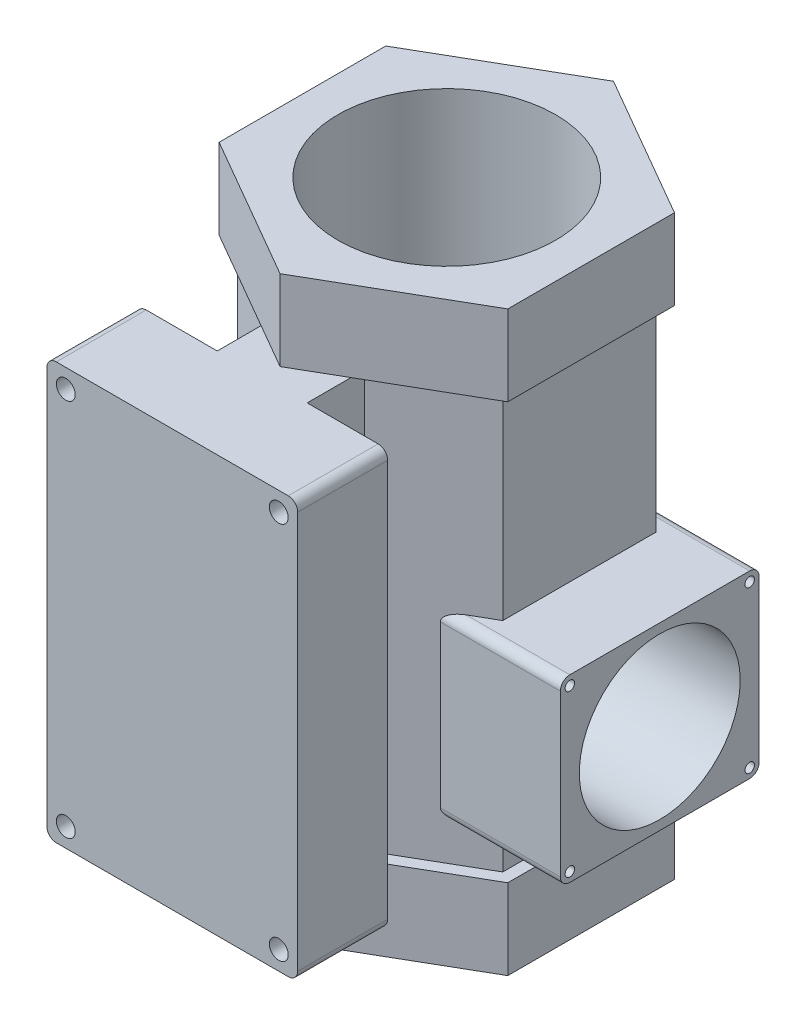
SolidWorks part; units mm, degrees
ref_plane "Спереди" through (0, 0, 0) normal (0, 0, 1) x (1, 0, 0)
ref_plane "Сверху" through (0, 0, 0) normal (0, 1, 0) x (1, 0, 0)
ref_plane "Справа" through (0, 0, 0) normal (1, 0, 0) x (0, 0, -1)
sketch "Эскиз центра" plane through (0, 0, 0) normal (0, 1, 0) x (1, 0, 0)
  line L0 (0, 0) -> (0, -290) construction
  line L1 (0, 161.6581) -> (-140, 80.829)
  line L2 (-140, 80.829) -> (-140, -80.829)
  line L3 (-140, -80.829) -> (-47.5, -134.2339)
  line L4 (47.5, -134.2339) -> (140, -80.829)
  line L5 (140, -80.829) -> (140, 80.829)
  line L6 (140, 80.829) -> (0, 161.6581)
  line L7 (132.5, -290) -> (-132.5, -290)
  line L8 (-132.5, -290) -> (-132.5, -195)
  line L9 (-132.5, -195) -> (-47.5, -195)
  line L10 (-47.5, -195) -> (-47.5, -134.2339)
  line L11 (47.5, -195) -> (47.5, -134.2339)
  line L12 (132.5, -195) -> (47.5, -195)
  line L13 (132.5, -290) -> (132.5, -195)
  circle A0 centre (0, 0) radius 140 construction
  dimension "D1" = 280
  dimension "D2" = 95
  dimension "D3" = 265
  dimension "D4" = 95
  dimension "D5" = 290
sketch "Эскиз2" plane through (0, 0, 0) normal (0, 1, 0) x (1, 0, 0)
  line L1 (0, 176.0918) -> (-152.5, 88.0459)
  line L2 (-152.5, 88.0459) -> (-152.5, -88.0459)
  line L3 (-152.5, -88.0459) -> (0, -176.0918)
  line L4 (0, -176.0918) -> (152.5, -88.0459)
  line L5 (152.5, -88.0459) -> (152.5, 88.0459)
  line L6 (152.5, 88.0459) -> (0, 176.0918)
  circle A0 centre (0, 0) radius 152.5 construction
  dimension "D1" = 305
extrude "Боковой многогранник 1" add sketch "Эскиз2" along normal blind 85
extrude "Центральная часть" add sketch "Эскиз центра" against normal blind 440
sketch "Эскиз4" plane through (0, -440, 0) normal (0, -1, 0) x (1, 0, 0)
  line L1 (0, -176.0918) -> (152.5, -88.0459)
  line L2 (152.5, -88.0459) -> (152.5, 88.0459)
  line L3 (152.5, 88.0459) -> (0, 176.0918)
  line L4 (0, 176.0918) -> (-152.5, 88.0459)
  line L5 (-152.5, 88.0459) -> (-152.5, -88.0459)
  line L6 (-152.5, -88.0459) -> (0, -176.0918)
  circle A0 centre (0, 0) radius 152.5 construction
extrude "Боковой многогранник 2" add sketch "Эскиз4" along normal blind 85
sketch "Эскиз5" plane through (0, 85, 0) normal (0, 1, 0) x (1, 0, 0)
  circle A0 centre (0, 0) radius 115
  dimension "D1" = 230
sketch "Эскиз10" plane through (140, 0, 0) normal (1, 0, 0) x (0, 0, -1)
  line L2 (-105, -210) -> (105, -210)
  line L3 (-105, -210) -> (-105, -400)
  line L4 (-105, -400) -> (105, -400)
  line L5 (105, -210) -> (105, -400)
  line L6 (-105, -210) -> (105, -400) construction
  line L7 (-105, -400) -> (105, -210) construction
  point P0 (0, -305)
  dimension "D1" = 190
  dimension "D2" = 210
extrude "Боковой фланц" add sketch "Эскиз10" along normal blind 85 and the other way blind 140
extrude "Центральный вырез" cut sketch "Эскиз5" against normal through all contours A0
sketch "Эскиз12" plane through (225, 0, 0) normal (1, 0, 0) x (0, 0, -1)
  circle A0 centre (0, -305) radius 85
  dimension "D1" = 170
extrude "Боковой вырез" cut sketch "Эскиз12" against normal up to next
sketch "Эскиз13" plane through (0, 0, 290) normal (0, 0, 1) x (1, 0, 0)
  line L0 (132.5, -440) -> (132.5, 0) construction
  line L1 (-132.5, 0) -> (132.5, 0) construction
  line L2 (-132.5, -440) -> (-132.5, 0) construction
  line L3 (-132.5, -440) -> (132.5, -440) construction
  circle A0 centre (-112.5, -420) radius 10
  circle A1 centre (112.5, -420) radius 10
  circle A2 centre (-112.5, -20) radius 10
  circle A3 centre (112.5, -20) radius 10
  dimension "D1" = 20
  dimension "D5" = 20
  dimension "D6" = 20
  dimension "D7" = 20
  dimension "D8" = 20
  dimension "D2" = 20
  dimension "D3" = 20
  dimension "D4" = 20
  dimension "D9" = 20
  dimension "D10" = 20
  dimension "D11" = 20
  dimension "D12" = 20
extrude "Отверстия в основании" cut sketch "Эскиз13" against normal up to next
sketch "Эскиз14" plane through (225, 0, 0) normal (1, 0, 0) x (0, 0, -1)
  line L0 (-105, -210) -> (-105, -400) construction
  line L1 (105, -210) -> (-105, -210) construction
  line L2 (105, -400) -> (105, -210) construction
  line L3 (-105, -400) -> (105, -400) construction
  line L4 (105, -400) -> (105, -210) construction
  circle A0 centre (95, -220) radius 5
  circle A1 centre (95, -390) radius 5
  circle A2 centre (-95, -220) radius 5
  circle A3 centre (-95, -390) radius 5
  dimension "D1" = 10
  dimension "D9" = 10
  dimension "D10" = 10
  dimension "D11" = 10
  dimension "D12" = 10
  dimension "D2" = 10
  dimension "D3" = 10
  dimension "D4" = 10
  dimension "D5" = 10
  dimension "D6" = 10
  dimension "D7" = 10
  dimension "D8" = 10
extrude "Вырез-Вытянуть6" cut sketch "Эскиз14" against normal blind 30
fillet "Скругление2" radius 10 4 edges at (-132.5, -440, 242.5) (132.5, -440, 242.5) (-132.5, 0, 242.5) (132.5, 0, 242.5)
fillet "Скругление3" radius 10 4 edges at (161.5673, -210, -105) (161.5673, -400, -105) (161.5673, -400, 105) (161.5673, -210, 105)
